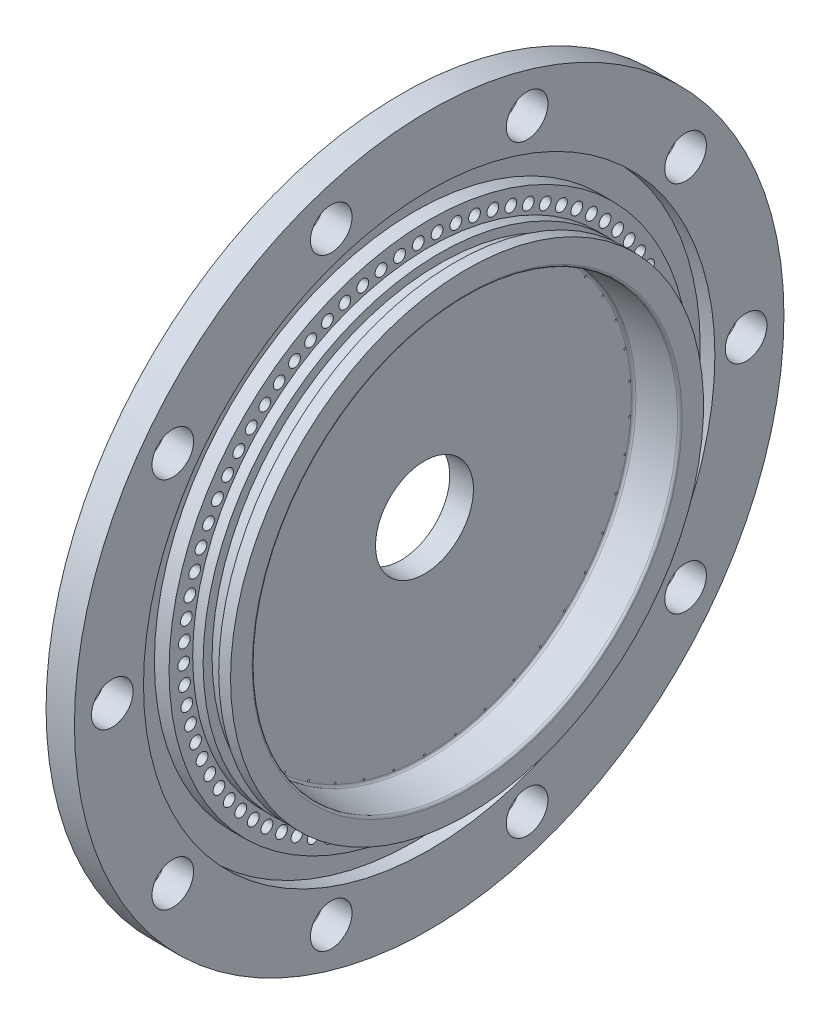
SolidWorks part; units mm, degrees
ref_plane "Front Plane" through (0, 0, 0) normal (0, 0, 1) x (1, 0, 0)
ref_plane "Top Plane" through (0, 0, 0) normal (0, 1, 0) x (1, 0, 0)
ref_plane "Right Plane" through (0, 0, 0) normal (1, 0, 0) x (0, 0, -1)
sketch "Sketch4" plane through (0, 0, 0) normal (0, 0, 1) x (1, 0, 0)
  line L0 (0, 0) -> (0, 42.055) construction
  line L1 (2.1534, 50) -> (36.2156, 50) construction
  line L2 (0, 10.35) -> (0, 75)
  line L3 (0, 75) -> (6, 75)
  line L4 (6, 75) -> (6, 60.4)
  line L5 (6, 50) -> (8.2, 50)
  line L6 (14, 50) -> (14, 45.4582)
  line L7 (13.5436, 44.9601) -> (5.4564, 44.2525)
  line L8 (0, 10.35) -> (5, 10.35)
  line L9 (5, 10.35) -> (5, 43.7544)
  line L10 (11.5, 50) -> (11.5, 48.1)
  line L11 (11.5, 48.1) -> (8.2, 48.1)
  line L12 (8.2, 48.1) -> (8.2, 50)
  line L13 (6, 55) -> (2.9, 55)
  line L14 (2.9, 55) -> (2.9, 60.4)
  line L15 (2.9, 60.4) -> (6, 60.4)
  line L16 (11.5, 50) -> (14, 50)
  line L17 (6, 55) -> (6, 50)
  line L18 (0, 0) -> (17.439, 0) construction
  arc A0 (14, 45.4582) -> (13.5436, 44.9601) centre (13.5, 45.4582) cw
  arc A1 (5.4564, 44.2525) -> (5, 43.7544) centre (5.5, 43.7544) ccw
  point P24 (14, 45)
  point P27 (5, 44.2126)
  dimension "D16" = 0.5
  dimension "D17" = 0.5
  dimension "D1" = 50
  dimension "D2" = 75
  dimension "D3" = 6
  dimension "D4" = 9
  dimension "D5" = 10.35
  dimension "D6" = 5
  dimension "D7" = 95
  dimension "D8" = 1.9
  dimension "D9" = 3.3
  dimension "D10" = 5
  dimension "D11" = 33.8626
  dimension "D12" = 3.1
  dimension "D13" = 5.4
  dimension "D14" = 55
  dimension "D15" = 2.5
revolve "Revolve2" add sketch "Sketch4" angle 360 about L18
sketch "Sketch5" plane through (6, 0, 0) normal (1, 0, 0) x (0, 0, -1)
  line L0 (0, 0) -> (0, 55.5529) construction
  line L1 (0, 0) -> (0, 51.9) construction
  line L2 (0, 0) -> (1.8113, 51.8684) construction
  line L3 (0, 0) -> (2.5152, 68.5935) construction
  circle A0 centre (0, 0) radius 51.9
  circle A1 centre (0, 51.9) radius 1.25 construction
  circle A2 centre (1.8113, 51.8684) radius 1.25 construction
  circle A3 centre (1.6755, 51.8729) radius 1.25
  point P6 (1.9018, 51.8651)
  point P16 (0, 0)
  dimension "D1" = 2
  dimension "D2" = 2
  dimension "D6" = 51.9
  dimension "D3" = 2
  dimension "D5" = 2.1
  dimension "D4" = 2
extrude "Cut-Extrude1" cut sketch "Sketch5" against normal through all and the other way through all
pattern_circular "CirPattern1" count 82 over 360 about axis through (0, 0, 0) along (1, 0, 0) of "Cut-Extrude1"
sketch "Sketch6" plane through (6, 0, 0) normal (1, 0, 0) x (0, 0, -1)
  line L0 (0, 0) -> (67, 0) construction
  line L1 (0, 0) -> (0, 67) construction
  circle A1 centre (0, 0) radius 67 construction
  circle A2 centre (67, 0) radius 4.4
  point P11 (0, 0)
  dimension "D1" = 90
  dimension "D2" = 67
extrude "Cut-Extrude2" cut sketch "Sketch6" against normal through all contours A1 A2 | A1 A2
pattern_circular "CirPattern2" count 10 over 360 about axis through (0, 0, 0) along (1, 0, 0) of "Cut-Extrude2"
sketch "Sketch9" plane through (5, 0, 0) normal (1, 0, 0) x (0, 0, -1)
  line L0 (0, 0) -> (0, 43.5)
  circle A0 centre (0, 43.5) radius 0.2
extrude "Cut-Extrude3" cut sketch "Sketch9" against normal up to next
sketch "Sketch10" plane through (0, 0, 0) normal (-1, 0, 0) x (0, 0, 1)
  circle A0 centre (0, 43.5) radius 0.7
extrude "Cut-Extrude4" cut sketch "Sketch10" against normal blind 3.8
pattern_circular "CirPattern3" count 42 over 360 about axis through (0, 0, 0) along (1, 0, 0) of "Cut-Extrude3", "Cut-Extrude4"
